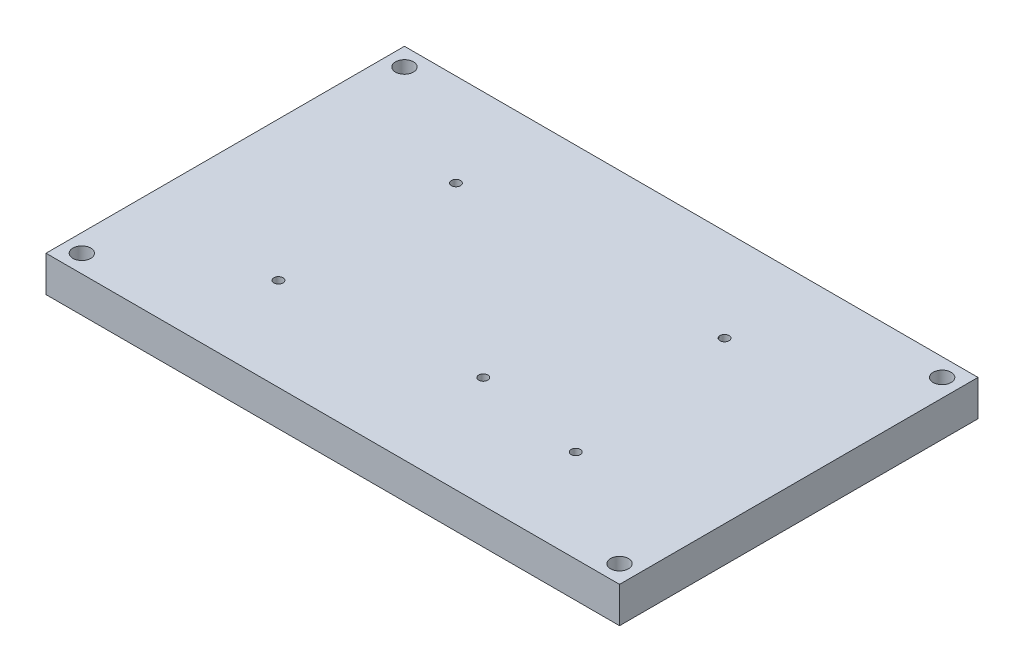
SolidWorks part; units mm, degrees
ref_plane "Plan de face" through (0, 0, 0) normal (0, 0, 1) x (1, 0, 0)
ref_plane "Plan de dessus" through (0, 0, 0) normal (0, 1, 0) x (1, 0, 0)
ref_plane "Plan de droite" through (0, 0, 0) normal (1, 0, 0) x (0, 0, -1)
sketch "Esquisse1" plane through (0, 0, 0) normal (0, 1, 0) x (1, 0, 0)
  line L1 (0, 0) -> (160, 0)
  line L2 (0, 0) -> (0, 100)
  line L3 (0, 100) -> (160, 100)
  line L4 (160, 0) -> (160, 100)
  circle A0 centre (5, 95) radius 2.5
  circle A1 centre (5, 5) radius 2.5
  circle A2 centre (155, 95) radius 2.5
  circle A3 centre (155, 5) radius 2.5
  dimension "D3" = 5
  dimension "D4" = 5
  dimension "D5" = 5
  dimension "D6" = 5
  dimension "D1" = 160
  dimension "D2" = 100
  dimension "D7" = 5
  dimension "D8" = 5
  dimension "D9" = 5
  dimension "D10" = 5
  dimension "D11" = 5
  dimension "D12" = 5
  dimension "D13" = 5
  dimension "D14" = 5
extrude "Boss.-Extru.1" add sketch "Esquisse1" along normal blind 10
sketch "Esquisse2" plane through (0, 10, 0) normal (0, 1, 0) x (1, 0, 0)
  line L8 (10, 90) -> (150, 90) construction
  line L9 (150, 90) -> (150, 10) construction
  line L10 (150, 10) -> (10, 10) construction
  line L11 (10, 10) -> (10, 90) construction
  line L12 (160, 0) -> (160, 100) construction
  line L13 (0, 0) -> (160, 0) construction
  line L14 (0, 100) -> (0, 0) construction
  line L15 (160, 100) -> (0, 100) construction
  line L17 (25, 76.67) -> (126.6, 76.67)
  line L18 (25, 76.67) -> (25, 23.33)
  line L19 (25, 23.33) -> (126.6, 23.33)
  line L20 (126.6, 76.67) -> (126.6, 23.33)
  circle A0 centre (40.24, 74.13) radius 1.27
  circle A1 centre (38.97, 25.87) radius 1.27
  circle A2 centre (91.04, 30.95) radius 1.27
  circle A3 centre (121.92, 25.87) radius 1.27
  circle A4 centre (115.17, 74.13) radius 1.27
  dimension "D9" = 2.54
  dimension "D10" = 2.54
  dimension "D11" = 2.54
  dimension "D12" = 2.54
  dimension "D13" = 2.54
  dimension "D1" = 10
  dimension "D2" = 10
  dimension "D3" = 10
  dimension "D4" = 10
  dimension "D5" = 101.6
  dimension "D6" = 53.34
  dimension "D7" = 15
  dimension "D8" = 13.33
  dimension "D14" = 2.54
  dimension "D15" = 13.97
  dimension "D16" = 2.54
  dimension "D17" = 96.92
  dimension "D18" = 7.62
  dimension "D19" = 66.04
  dimension "D20" = 2.54
  dimension "D21" = 90.17
  dimension "D22" = 15.24
  dimension "D23" = 50.8
extrude "Enlèv. mat.-Extru.1" cut sketch "Esquisse2" against normal through all contours A1 | A2 | A3 | A4 | A0
